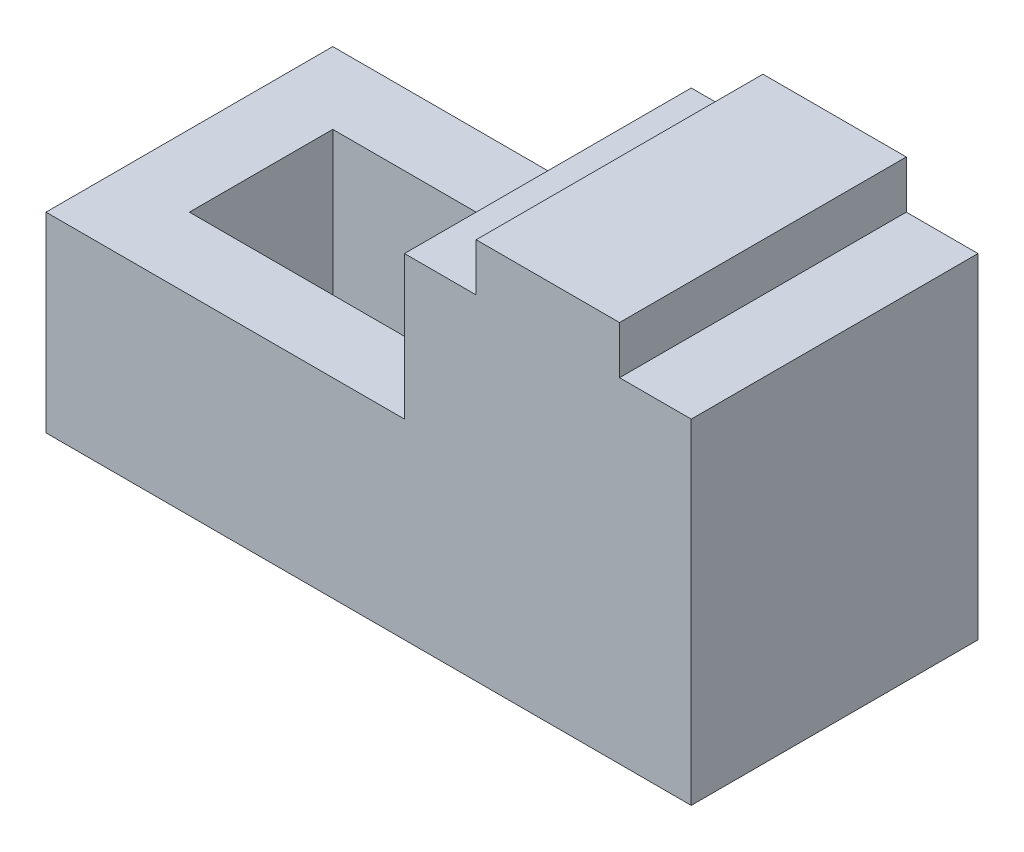
SolidWorks part; units mm, degrees
ref_plane "Front Plane" through (0, 0, 0) normal (0, 0, 1) x (1, 0, 0)
ref_plane "Top Plane" through (0, 0, 0) normal (0, 1, 0) x (1, 0, 0)
ref_plane "Right Plane" through (0, 0, 0) normal (1, 0, 0) x (0, 0, -1)
sketch "Sketch1" plane through (0, 0, 0) normal (0, 0, 1) x (1, 0, 0)
  line L0 (0, 0) -> (108, 0)
  line L1 (108, 0) -> (108, 56)
  line L2 (108, 56) -> (96, 56)
  line L3 (96, 56) -> (96, 64)
  line L4 (96, 64) -> (72, 64)
  line L5 (72, 64) -> (72, 56)
  line L6 (72, 56) -> (60, 56)
  line L7 (60, 56) -> (60, 32)
  line L8 (60, 32) -> (0, 32)
  line L9 (0, 32) -> (0, 0)
  dimension "D1" = 108
  dimension "D2" = 56
  dimension "D3" = 8
  dimension "D4" = 24
  dimension "D5" = 32
  dimension "D6" = 8
  dimension "D7" = 12
  dimension "D8" = 12
extrude "Boss-Extrude1" add sketch "Sketch1" along normal blind 48 contours L9 L0 L1 L2 L3 L4 L5 L6 L7 L8
sketch "Sketch2" plane through (0, 0, 48) normal (0, 0, 1) x (1, 0, 0)
  line L0 (72, 32) -> (96, 32)
  line L1 (96, 32) -> (96, 48)
  line L2 (96, 48) -> (72, 48)
  line L3 (72, 48) -> (72, 32)
  dimension "D1" = 16
sketch "Sketch4" plane through (0, 32, 0) normal (0, 1, 0) x (1, 0, 0)
  line L1 (60, -48) -> (60, 0) construction
  line L2 (60, -12) -> (12, -12)
  line L3 (12, -12) -> (12, -36)
  line L4 (12, -36) -> (60, -36)
  line L5 (60, -36) -> (60, -12)
  dimension "D2" = 24
  dimension "D3" = 48
extrude "Cut-Extrude1" cut sketch "Sketch4" against normal blind 24 contours L2 L3 L4 L5
